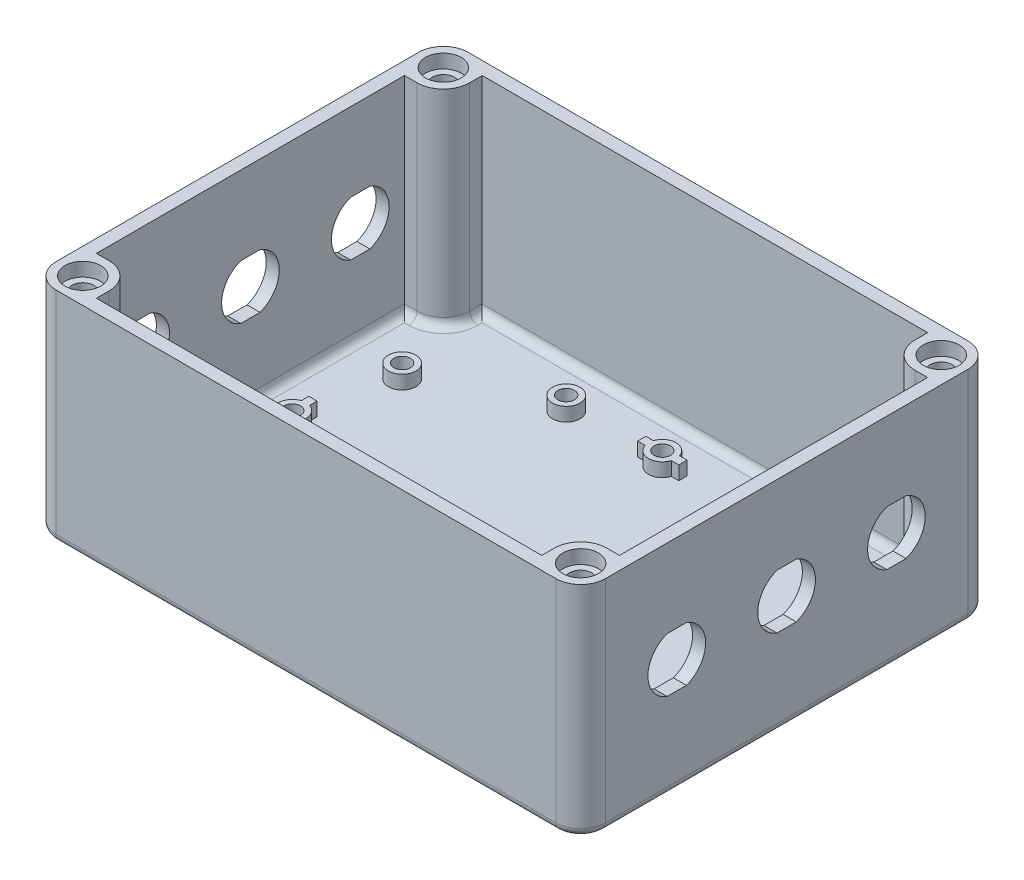
SolidWorks part; units mm, degrees
ref_plane "Front Plane" through (0, 0, 0) normal (0, 0, 1) x (1, 0, 0)
ref_plane "Top Plane" through (0, 0, 0) normal (0, 1, 0) x (1, 0, 0)
ref_plane "Right Plane" through (0, 0, 0) normal (1, 0, 0) x (0, 0, -1)
sketch "Sketch1" plane through (0, 0, 0) normal (0, 1, 0) x (1, 0, 0)
  line L1 (0, 0) -> (200, 0)
  line L2 (0, 0) -> (0, 150)
  line L3 (0, 150) -> (200, 150)
  line L4 (200, 0) -> (200, 150)
  dimension "D1" = 200
  dimension "D2" = 150
extrude "Boss-Extrude1" add sketch "Sketch1" along normal blind 5
sketch "Sketch2" plane through (0, 5, 0) normal (0, 1, 0) x (1, 0, 0)
  line L0 (0, 0) -> (18.9, 18.9) construction
  line L1 (0, 0) -> (200, 0)
  line L2 (0, 0) -> (0, 150)
  line L3 (0, 150) -> (200, 150)
  line L4 (200, 0) -> (200, 150)
  line L5 (4.75, 4.75) -> (195.25, 4.75)
  line L6 (4.75, 4.75) -> (4.75, 145.25)
  line L7 (4.75, 145.25) -> (195.25, 145.25)
  line L8 (195.25, 4.75) -> (195.25, 145.25)
  line L9 (4.75, 145.25) -> (18.9, 145.25) construction
  line L10 (4.75, 145.25) -> (4.75, 131.1) construction
  line L11 (4.75, 131.1) -> (18.9, 131.1) construction
  line L12 (18.9, 145.25) -> (18.9, 131.1) construction
  line L13 (195.25, 145.25) -> (181.1, 145.25) construction
  line L14 (195.25, 145.25) -> (195.25, 131.1) construction
  line L15 (195.25, 131.1) -> (181.1, 131.1) construction
  line L16 (181.1, 145.25) -> (181.1, 131.1) construction
  line L17 (4.75, 4.75) -> (18.9, 4.75) construction
  line L18 (4.75, 4.75) -> (4.75, 18.9) construction
  line L19 (4.75, 18.9) -> (18.9, 18.9) construction
  line L20 (18.9, 4.75) -> (18.9, 18.9) construction
  line L21 (195.25, 4.75) -> (181.1, 4.75) construction
  line L22 (195.25, 4.75) -> (195.25, 18.9) construction
  line L23 (195.25, 18.9) -> (181.1, 18.9) construction
  line L24 (181.1, 4.75) -> (181.1, 18.9) construction
  line L25 (4.75, 18.9) -> (9.3462, 18.9)
  line L26 (18.9, 4.75) -> (18.9, 9.3462)
  line L27 (0, 75) -> (200, 75) construction
  line L28 (100, 150) -> (100, 0) construction
  line L29 (181.1, 4.75) -> (181.1, 9.3462)
  line L30 (195.25, 18.9) -> (190.6538, 18.9)
  line L31 (18.9, 145.25) -> (18.9, 140.6538)
  line L32 (4.75, 131.1) -> (9.3462, 131.1)
  line L33 (181.1, 145.25) -> (181.1, 140.6538)
  line L34 (195.25, 131.1) -> (190.6538, 131.1)
  arc A3 (18.9, 9.3462) -> (9.3462, 18.9) centre (9.3462, 9.3462) ccw
  circle A4 centre (9.3462, 9.3462) radius 6.5 construction
  circle A5 centre (9.3462, 9.3462) radius 4
  circle A6 centre (190.6538, 9.3462) radius 4
  arc A7 (181.1, 9.3462) -> (190.6538, 18.9) centre (190.6538, 9.3462) cw
  circle A8 centre (9.3462, 140.6538) radius 4
  arc A9 (18.9, 140.6538) -> (9.3462, 131.1) centre (9.3462, 140.6538) cw
  circle A10 centre (190.6538, 140.6538) radius 4
  arc A11 (181.1, 140.6538) -> (190.6538, 131.1) centre (190.6538, 140.6538) ccw
  point P10 (100, 145.25)
  point P11 (100, 150)
  point P12 (0, 75)
  point P13 (4.75, 75)
  line M40 (0, 150) -> (0, 0)
  line M41 (0, 0) -> (200, 0)
  line M42 (200, 0) -> (200, 150)
  line M43 (200, 150) -> (0, 150)
  dimension "D4" = 13
  dimension "D5" = 8
  dimension "D1" = 190.5
  dimension "D2" = 140.5
  dimension "D3" = 162.2
extrude "Boss-Extrude2" add sketch "Sketch2" along normal blind 75 contours A9 L31 L7 L6 L32 A8 | L8 L5 L6 L7 M43 M40 M41 M42 | L33 A11 L34 L8 L7 A10 | A7 L29 L5 L8 L30 A6 | L26 A3 L25 L6 L5 A5
sketch "Sketch3" plane through (0, 80, 0) normal (0, 1, 0) x (1, 0, 0)
  circle A0 centre (9.3462, 140.6538) radius 6.5
  circle A1 centre (190.6538, 140.6538) radius 6.5
  circle A2 centre (190.6538, 9.3462) radius 6.5
  circle A3 centre (9.3462, 9.3462) radius 6.5
  dimension "D1" = 13
extrude "Cut-Extrude1" cut sketch "Sketch3" against normal blind 5
fillet "Fillet1" radius 9 4 edges at (200, 40, -150) (200, 40, 0) (0, 40, 0) (0, 40, -150)
sketch "Sketch4" plane through (0, 5, 0) normal (0, 1, 0) x (1, 0, 0)
  line L0 (100, 150) -> (100, 129.75) construction
  line L1 (25, 129.75) -> (175, 129.75) construction
  line L2 (25, 129.75) -> (25, 20.25) construction
  line L3 (25, 20.25) -> (175, 20.25) construction
  line L4 (175, 129.75) -> (175, 20.25) construction
  line L5 (191, 150) -> (9, 150) construction
  line L6 (181.5, 67.5) -> (178.5, 67.5)
  line L7 (25, 75) -> (0, 75) construction
  line L8 (0, 141) -> (0, 9) construction
  line L9 (92.5, 131.25) -> (107.5, 131.25)
  line L10 (92.5, 131.25) -> (92.5, 128.25)
  line L11 (92.5, 128.25) -> (107.5, 128.25)
  line L12 (107.5, 131.25) -> (107.5, 128.25)
  line L13 (18.5, 82.5) -> (21.5, 82.5)
  line L14 (18.5, 82.5) -> (18.5, 67.5)
  line L15 (18.5, 67.5) -> (21.5, 67.5)
  line L16 (21.5, 82.5) -> (21.5, 67.5)
  line L17 (92.5, 21.75) -> (107.5, 21.75)
  line L18 (92.5, 21.75) -> (92.5, 18.75)
  line L19 (92.5, 18.75) -> (107.5, 18.75)
  line L20 (107.5, 21.75) -> (107.5, 18.75)
  line L21 (178.5, 82.5) -> (178.5, 67.5)
  line L22 (181.5, 82.5) -> (178.5, 82.5)
  line L23 (181.5, 82.5) -> (181.5, 67.5)
  circle A0 centre (100, 129.75) radius 3
  circle A1 centre (65, 129.75) radius 3
  circle A2 centre (25, 110) radius 3
  circle A3 centre (25, 40) radius 3
  circle A4 centre (65, 20.25) radius 3
  circle A5 centre (100, 20.25) radius 3
  circle A6 centre (65, 129.75) radius 5
  circle A7 centre (100, 129.75) radius 5
  circle A8 centre (25, 110) radius 5
  circle A9 centre (25, 40) radius 5
  circle A10 centre (65, 20.25) radius 5
  circle A11 centre (100, 20.25) radius 5
  circle A12 centre (20, 75) radius 3
  circle A13 centre (20, 75) radius 5
  circle A14 centre (135, 20.25) radius 3
  circle A15 centre (135, 20.25) radius 5
  circle A16 centre (175, 40) radius 3
  circle A17 centre (175, 40) radius 5
  circle A18 centre (180, 75) radius 3
  circle A19 centre (180, 75) radius 5
  circle A20 centre (175, 110) radius 3
  circle A21 centre (175, 110) radius 5
  circle A22 centre (135, 129.75) radius 5
  circle A23 centre (135, 129.75) radius 3
  point P36 (92.5, 129.75)
  point P37 (100, 131.25)
  point P42 (92.5, 20.25)
  point P43 (20, 82.5)
  point P44 (18.5, 75)
  point P49 (100, 21.75)
  dimension "D5" = 6
  dimension "D6" = 10
  dimension "D8" = 80
  dimension "D1" = 150
  dimension "D2" = 109.5
  dimension "D3" = 70
  dimension "D4" = 35
  dimension "D7" = 35
  dimension "D9" = 15
  dimension "D10" = 3
  dimension "D11" = 3
  dimension "D12" = 3
extrude "Boss-Extrude3" add sketch "Sketch4" along normal blind 5 contours A6 A1 | A8 A2 | A13 L16 L13 L14 | L16 A13 L14 A12 | L14 A13 A12 | L16 A13 A12 | L14 A13 L16 A12 | A13 L14 L15 L16 | A9 A3 | A10 A4 | L17 A11 A5 | L17 A11 L19 A5 | A11 L17 L18 L19 | L19 A11 A5 | A11 L19 L20 L17 | L19 A11 L17 A5 | A15 A14 | A17 A16 | L21 A19 L23 L22 | A19 L21 A18 | A19 L21 A18 L23 | A19 L23 A18 | A19 L23 A18 L21 | L23 A19 L21 L6 | A21 A20 | A22 A23 | L9 A7 A0 | A7 L11 L12 L9 | L11 A7 L9 A0 | L9 A7 L11 A0 | A7 L9 L10 L11 | L11 A7 A0
fillet "Fillet2" radius 3 16 edges at (183.8982, 5, -16.1018) (181.1, 5, -7.0481) (100, 5, -4.75) (18.9, 5, -7.0481) (16.1018, 5, -16.1018) (7.0481, 5, -18.9) (4.75, 5, -75) (7.0481, 5, -131.1) (16.1018, 5, -133.8982) (18.9, 5, -142.9519) (100, 5, -145.25) (181.1, 5, -142.9519) (183.8982, 5, -133.8982) (192.9519, 5, -131.1) (195.25, 5, -75) (192.9519, 5, -18.9)
fillet "Fillet3" radius 3 8 edges at (2.636, 0, -147.364) (0, 0, -75) (2.636, 0, -2.636) (100, 0, 0) (197.364, 0, -2.636) (200, 0, -75) (197.364, 0, -147.364) (100, 0, -150)
sketch "Sketch5" plane through (0, 0, 0) normal (-1, 0, 0) x (0, 0, 1)
  line L0 (-75, 80) -> (-75, 3) construction
  line L1 (-141, 80) -> (-9, 80) construction
  line L2 (-141, 3) -> (-9, 3) construction
  line L3 (-118.4986, 51.4) -> (-111.5014, 51.4)
  line L4 (-118.4986, 31.6) -> (-111.5014, 31.6)
  line L5 (-78.4986, 51.4) -> (-71.5014, 51.4)
  line L6 (-78.4986, 31.6) -> (-71.5014, 31.6)
  line L7 (-31.5014, 31.6) -> (-38.4986, 31.6)
  line L8 (-31.5014, 51.4) -> (-38.4986, 51.4)
  circle A0 centre (-75, 41.5) radius 14.5 construction
  circle A1 centre (-115, 41.5) radius 14.5 construction
  arc A2 (-78.4986, 51.4) -> (-78.4986, 31.6) centre (-75, 41.5) ccw
  arc A3 (-118.4986, 51.4) -> (-118.4986, 31.6) centre (-115, 41.5) ccw
  arc A4 (-111.5014, 31.6) -> (-111.5014, 51.4) centre (-115, 41.5) ccw
  arc A5 (-71.5014, 31.6) -> (-71.5014, 51.4) centre (-75, 41.5) ccw
  arc A6 (-31.5014, 51.4) -> (-31.5014, 31.6) centre (-35, 41.5) cw
  arc A7 (-38.4986, 31.6) -> (-38.4986, 51.4) centre (-35, 41.5) cw
  point P16 (0, 0)
  point P17 (0, 0)
  point P18 (0, 0)
  point P19 (0, 0)
  point P20 (0, 0)
  dimension "D1" = 29
  dimension "D2" = 21
  dimension "D3" = 40
  dimension "D4" = 19.8
extrude "Cut-Extrude2" cut sketch "Sketch5" against normal through all
